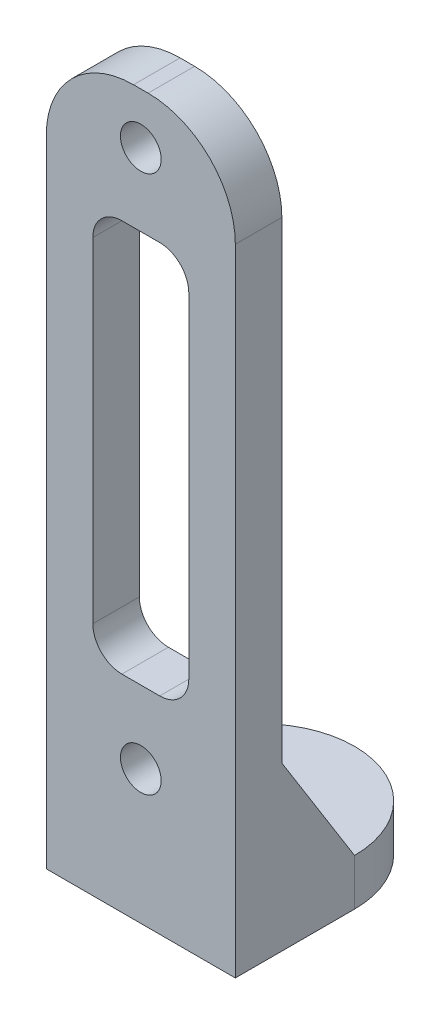
SolidWorks part; units mm, degrees
ref_plane "Front Plane" through (0, 0, 0) normal (0, 0, 1) x (1, 0, 0)
ref_plane "Top Plane" through (0, 0, 0) normal (0, 1, 0) x (1, 0, 0)
ref_plane "Right Plane" through (0, 0, 0) normal (1, 0, 0) x (0, 0, -1)
sketch "Sketch1" plane through (0, 0, 0) normal (0, 0, 1) x (1, 0, 0)
  line L0 (6.5, 0) -> (6.5, 6) construction
  line L1 (0, 0) -> (13, 0)
  line L2 (0, 0) -> (0, 40.5)
  line L3 (6, 46.5) -> (7, 46.5)
  line L4 (13, 0) -> (13, 40.5)
  circle A0 centre (6.5, 6) radius 1.4
  circle A1 centre (6.5, 43) radius 1.4
  arc A2 (7, 46.5) -> (13, 40.5) centre (7, 40.5) cw
  arc A3 (0, 40.5) -> (6, 46.5) centre (6, 40.5) cw
  dimension "D3" = 2.8
  dimension "D7" = 6
  dimension "D1" = 13
  dimension "D2" = 46.5
  dimension "D4" = 6
  dimension "D6" = 37
  dimension "D5" = 2
extrude "Boss-Extrude1" add sketch "Sketch1" along normal blind 3.2
sketch "Sketch2" plane through (0, 0, 0) normal (0, 1, 0) x (1, 0, 0)
  line L0 (0, 5) -> (0, -3.2)
  line L1 (0, -3.2) -> (13, -3.2)
  line L3 (13, -3.2) -> (13, 5)
  line L4 (7, 0) -> (6, 0) construction
  circle A0 centre (6.5, 5) radius 1.65
  arc A1 (13, 5) -> (0, 5) centre (6.5, 5) ccw
  dimension "D1" = 3.3
  dimension "D2" = 5
extrude "Boss-Extrude3" add sketch "Sketch2" against normal blind 3.2
sketch "Sketch3" plane through (0, 0, 0) normal (1, 0, 0) x (0, 0, -1)
  line L0 (0, 0) -> (5, 0)
  line L2 (5, 0) -> (0, 8)
  line L4 (0, 8) -> (0, 0)
  dimension "D1" = 8
extrude "Boss-Extrude4" add sketch "Sketch3" along normal blind 2
pattern_linear "LPattern1" count 2 spacing 11 along (1, 0, 0) of "Boss-Extrude4"
sketch "Sketch4" plane through (0, 0, 0) normal (0, 0, 1) x (1, 0, 0)
  line L0 (0, 40.5) -> (0, -3.2) construction
  line L1 (5.2, 38) -> (7.8, 38)
  line L2 (3.2, 36) -> (3.2, 13)
  line L3 (5.2, 11) -> (7.8, 11)
  line L4 (9.8, 36) -> (9.8, 13)
  line L5 (13, -3.2) -> (13, 40.5) construction
  circle A0 centre (6.5, 6) radius 1.4 construction
  circle A1 centre (6.5, 43) radius 1.4 construction
  arc A2 (3.2, 13) -> (5.2, 11) centre (5.2, 13) ccw
  arc A3 (7.8, 11) -> (9.8, 13) centre (7.8, 13) ccw
  arc A4 (7.8, 38) -> (9.8, 36) centre (7.8, 36) cw
  arc A5 (5.2, 38) -> (3.2, 36) centre (5.2, 36) ccw
  dimension "D3" = 5
  dimension "D5" = 2
  dimension "D1" = 3.2
  dimension "D2" = 3.2
  dimension "D4" = 5
extrude "Cut-Extrude1" cut sketch "Sketch4" along normal through all
